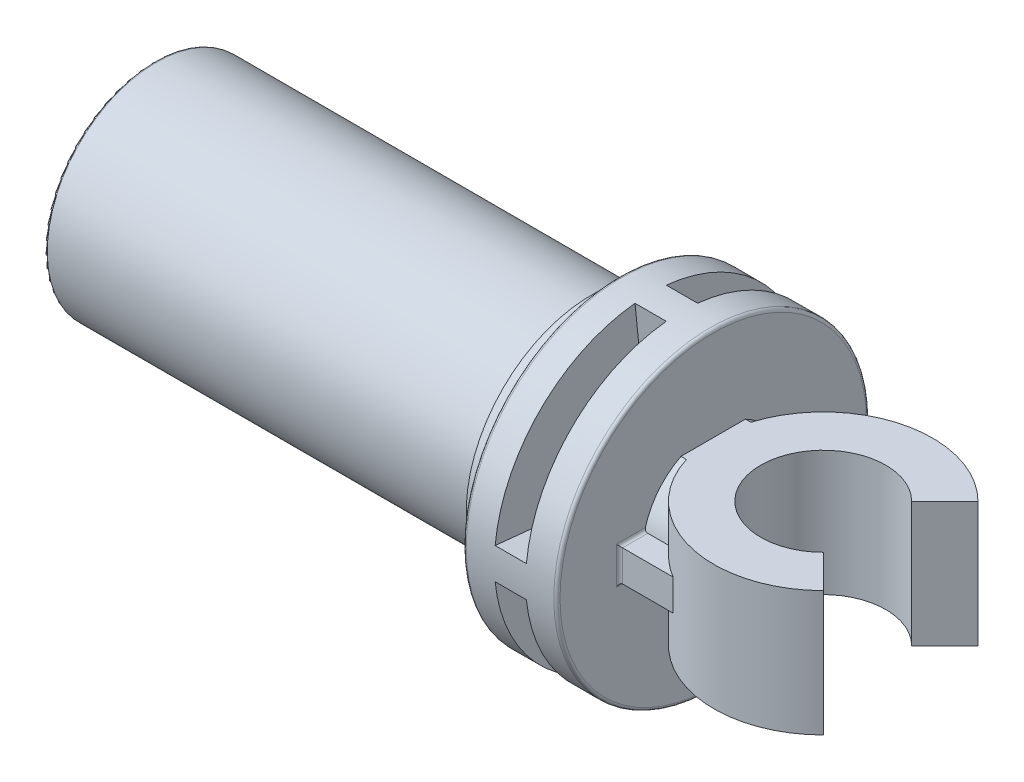
SolidWorks part; units mm, degrees
material "ABS PC"
ref_plane "Piano frontale" through (0, 0, 0) normal (0, 0, 1) x (1, 0, 0)
ref_plane "Piano superiore" through (0, 0, 0) normal (0, 1, 0) x (1, 0, 0)
ref_plane "Piano destro" through (0, 0, 0) normal (1, 0, 0) x (0, 0, -1)
sketch "Schizzo1" plane through (0, 0, 0) normal (1, 0, 0) x (0, 0, -1)
  circle A0 centre (0, 0) radius 3.5
  dimension "D1" = 7
extrude "Estrusione-Estrusione1" add sketch "Schizzo1" along normal blind 14
sketch "Schizzo2" plane through (14, 0, 0) normal (1, 0, 0) x (0, 0, -1)
  circle A0 centre (0, 0) radius 4
  dimension "D1" = 8
extrude "Estrusione-Estrusione2" add sketch "Schizzo2" along normal blind 0.9
sketch "Schizzo3" plane through (14.9, 0, 0) normal (1, 0, 0) x (0, 0, -1)
  circle A0 centre (0, 0) radius 5
  dimension "D1" = 10
extrude "Estrusione-Estrusione3" add sketch "Schizzo3" along normal blind 1
sketch "Schizzo4" plane through (15.9, 0, 0) normal (1, 0, 0) x (0, 0, -1)
  circle A0 centre (0, 0) radius 3.5
  dimension "D1" = 7
extrude "Estrusione-Estrusione4" add sketch "Schizzo4" along normal blind 1
sketch "Schizzo5" plane through (16.9, 0, 0) normal (1, 0, 0) x (0, 0, -1)
  circle A0 centre (0, 0) radius 5
  dimension "D1" = 10
extrude "Estrusione-Estrusione5" add sketch "Schizzo5" along normal blind 1
sketch "Schizzo6" plane through (0, 0, 0) normal (0, 1, 0) x (1, 0, 0)
  line L0 (15.9, 5) -> (14.9, 5) construction
  line L1 (15.9, 5) -> (16.9, 5)
  line L2 (15.9, 5) -> (15.9, 3)
  line L3 (15.9, 3) -> (16.9, 3)
  line L4 (16.9, 5) -> (16.9, 3)
  line L5 (16.9, 5) -> (16.9, -5) construction
  line L6 (0, 0) -> (21.8316, 0) construction
  dimension "D1" = 2
revolve "Rivoluzione1" add sketch "Schizzo6" angle 11.5 mid plane about L6
pattern_circular "RipetizioneCircolare1" count 4 over 360 of "Rivoluzione1"
sketch "Schizzo8" plane through (0, 0, 0) normal (-1, 0, 0) x (0, 0, 1)
  circle A0 centre (0, 0) radius 3
  dimension "D1" = 6
extrude "Taglio-Estrusione2" cut sketch "Schizzo8" against normal up to surface (14.9 mm away) up to face at (14.9, 0, -4)
sketch "Schizzo10" plane through (0, 0, 0) normal (0, 1, 0) x (1, 0, 0)
  line L0 (0, 3.5) -> (0, -3.5) construction
  line L1 (4, -1) -> (14.9, -1)
  line L2 (4, -1) -> (4, 1)
  line L3 (4, 1) -> (14.9, 1)
  line L4 (14.9, -1) -> (14.9, 1)
  line L5 (14.9, 5) -> (14.9, -5) construction
  line L6 (0, 0) -> (18.4594, 0) construction
  dimension "D1" = 4
  dimension "D2" = 2
  dimension "D3" = 1
extrude "Taglio-Estrusione3" cut sketch "Schizzo10" against normal through all
sketch "Schizzo11" plane through (14.9, 0, 0) normal (-1, 0, 0) x (0, 0, 1)
  circle A0 centre (0, 0) radius 2
  dimension "D1" = 4
extrude "Taglio-Estrusione5" cut sketch "Schizzo11" against normal up to surface (1 mm away) up to face at (15.9, 2.6662, -2.6662)
sketch "Schizzo12" plane through (17.9, 0, 0) normal (1, 0, 0) x (0, 0, -1)
  circle A0 centre (0, 0) radius 2.25
  dimension "D1" = 4.5
extrude "Estrusione-Estrusione14" add sketch "Schizzo12" along normal blind 1
sketch "Schizzo13" plane through (0, 0, 0) normal (0, 1, 0) x (1, 0, 0)
  line L0 (17.9, -5) -> (28.9692, -5) construction
  line L5 (22.8365, 1.4105) -> (23.9, 2.4683)
  line L6 (0, 0) -> (28.9692, 0) construction
  line L7 (0, 3.5) -> (0, -3.5) construction
  line L8 (17.9, -5) -> (17.9, 5) construction
  line L9 (24.9372, -3.5) -> (17.9, -3.5) construction
  line L10 (24.9372, -3.5) -> (24.9372, 3.5) construction
  line L11 (24.9372, 3.5) -> (17.9, 3.5) construction
  line L12 (17.9, -3.5) -> (17.9, 3.5) construction
  line L13 (24.9372, -3.5) -> (17.9, 3.5) construction
  line L14 (24.9372, 3.5) -> (17.9, -3.5) construction
  line L15 (22.8365, -1.4105) -> (23.9, -2.4683)
  arc A0 (22.8365, 1.4105) -> (22.8365, -1.4105) centre (21.4186, 0) ccw
  arc A1 (23.9, 2.4683) -> (23.9, -2.4683) centre (21.4186, 0) ccw
  point P1 (21.4186, 0)
  point P16 (0, 0)
  point P19 (0, 0)
  dimension "D3" = 3.5
  dimension "D4" = 2
  dimension "D1" = 1.5
  dimension "D2" = 6
extrude "Estrusione-Estrusione18" add sketch "Schizzo13" along normal mid plane 4
sketch "Schizzo14" plane through (0, 0, 0) normal (0, 1, 0) x (1, 0, 0)
  line L0 (17.9, 0) -> (17.9, 3)
  line L1 (17.9, -5) -> (17.9, 5) construction
  line L2 (17.9, 3) -> (19.6158, 3)
  line L3 (17.9, 0) -> (19.6158, 3)
  arc A3 (23.9, 2.4683) -> (18.0738, 1.0308) centre (21.4186, 0) ccw construction
  point P4 (0, 0)
  point P6 (20.672, 4)
  point P7 (20.8384, 4)
  point P8 (21.3408, 4)
  point P9 (0, 0)
  point P10 (19.6158, 3)
  point P11 (21.4186, 3.5)
  point P12 (0, 0)
  point P15 (20.5801, 3.3981)
  point P16 (0, 0)
  point P18 (0, 0)
  dimension "D1" = 3
extrude "Estrusione-Estrusione15" add sketch "Schizzo14" along normal mid plane 1
mirror "Specchia2" about plane through (0, 0, 0) normal (0, 0, 1) of "Estrusione-Estrusione15"
sketch "Schizzo15" plane through (0, 2, 0) normal (0, 1, 0) x (1, 0, 0)
  line L0 (17.9, -2.1937) -> (17.9, 2.1937) construction
  line L1 (18.9, -1.0308) -> (17.9, -1.0308)
  line L2 (18.9, -1.0308) -> (18.9, 1.0308)
  line L3 (18.9, 1.0308) -> (17.9, 1.0308)
  line L4 (17.9, -1.0308) -> (17.9, 1.0308)
  line L7 (18.9, -1.0308) -> (18.9, 1.0308) construction
  line L8 (18.9, 1.0308) -> (18.0738, 1.0308) construction
  line L10 (18.0738, -1.0308) -> (18.9, -1.0308) construction
extrude "Taglio-Estrusione6" cut sketch "Schizzo15" along normal blind 1
mirror "Specchia3" about plane through (0, 0, 0) normal (0, 1, 0) of "Taglio-Estrusione6"
fillet "Raccordo1" radius 0.1 2 edges at (17.9, 0, -5) (14.9, 0, -5)
fillet "Raccordo4" radius 0.1 6 edges at (17.9, 0.5, 2.5969) (17.9, 0.5, -2.5969) (17.9, 0, -3) (17.9, -0.5, -2.5969) (17.9, 0, 3) (17.9, -0.5, 2.5969)
fillet "Raccordo5" radius 0.1 1 edges at (0, 0, -3.5)
fillet "Raccordo6" radius 0.1 1 edges at (0, 0, 3)
fillet "Raccordo7" radius 0.1 1 edges at (14, 3.5, 0)
